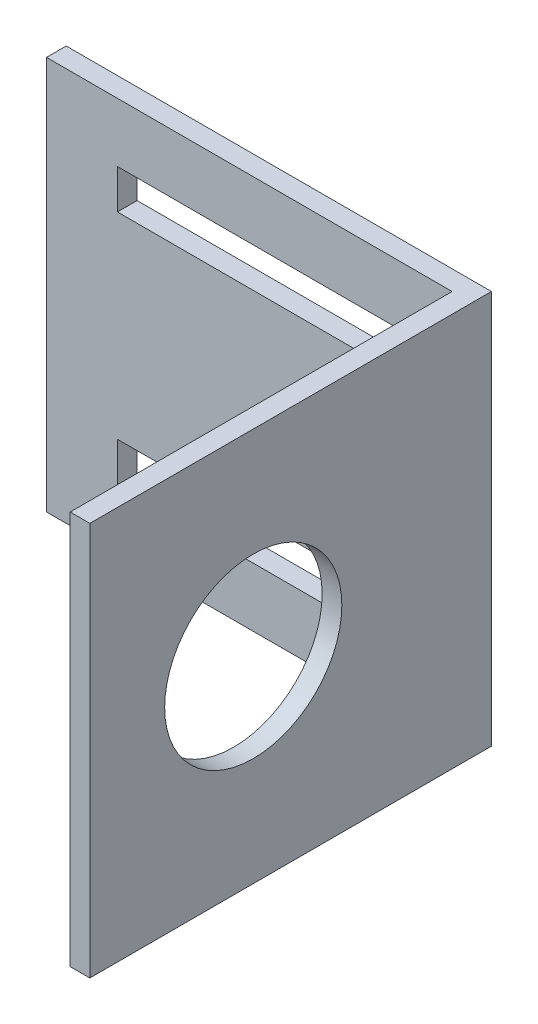
SolidWorks part; units mm, degrees
material "Custom Plastic"
ref_plane "Front Plane" through (0, 0, 0) normal (0, 0, 1) x (1, 0, 0)
ref_plane "Top Plane" through (0, 0, 0) normal (0, 1, 0) x (1, 0, 0)
ref_plane "Right Plane" through (0, 0, 0) normal (1, 0, 0) x (0, 0, -1)
sketch "Sketch1" plane through (0, 0, 0) normal (0, 0, 1) x (1, 0, 0)
  line L1 (-27, -25) -> (27, -25)
  line L2 (-27, -25) -> (-27, 25)
  line L3 (-27, 25) -> (27, 25)
  line L4 (27, -25) -> (27, 25)
  line L5 (-27, -25) -> (27, 25) construction
  line L6 (-27, 25) -> (27, -25) construction
  point P0 (0, 0)
extrude "Boss-Extrude1" add sketch "Sketch1" along normal blind 2.5
sketch "Sketch2" plane through (0, 0, 0) normal (0, 0, 1) x (1, 0, 0)
  line L0 (-27, -25) -> (27, -25) construction
  line L1 (27, 25) -> (24.5, 25)
  line L2 (27, 25) -> (27, -25)
  line L3 (27, -25) -> (24.5, -25)
  line L4 (24.5, 25) -> (24.5, -25)
extrude "Boss-Extrude2" add sketch "Sketch2" along normal blind 51
sketch "Sketch3" plane through (0, 0, 0) normal (1, 0, 0) x (0, 0, -1)
  line L2 (-19, 0) -> (-41.5, 0) construction
  circle A0 centre (-30.25, 0) radius 11.25
extrude "Cut-Extrude1" cut sketch "Sketch3" along normal blind 51
sketch "Sketch4" plane through (0, 0, 0) normal (0, 0, 1) x (1, 0, 0)
  line L0 (-18, 25) -> (-18, 17.5) construction
  line L1 (24.5, 25) -> (-27, 25) construction
  line L2 (-18, 17.5) -> (-27, 17.5) construction
  line L3 (-27, 25) -> (-27, -25) construction
  line L4 (0, 0) -> (10.9181, 0) construction
  line L5 (-18, 17.5) -> (17, 17.5)
  line L6 (-18, 17.5) -> (-18, 12.5)
  line L7 (-18, 12.5) -> (17, 12.5)
  line L8 (17, 17.5) -> (17, 12.5)
  line L9 (17, -17.5) -> (17, -12.5)
  line L10 (-18, -12.5) -> (17, -12.5)
  line L11 (-18, -17.5) -> (-18, -12.5)
  line L12 (-18, -17.5) -> (17, -17.5)
extrude "Cut-Extrude2" cut sketch "Sketch4" along normal blind 51
